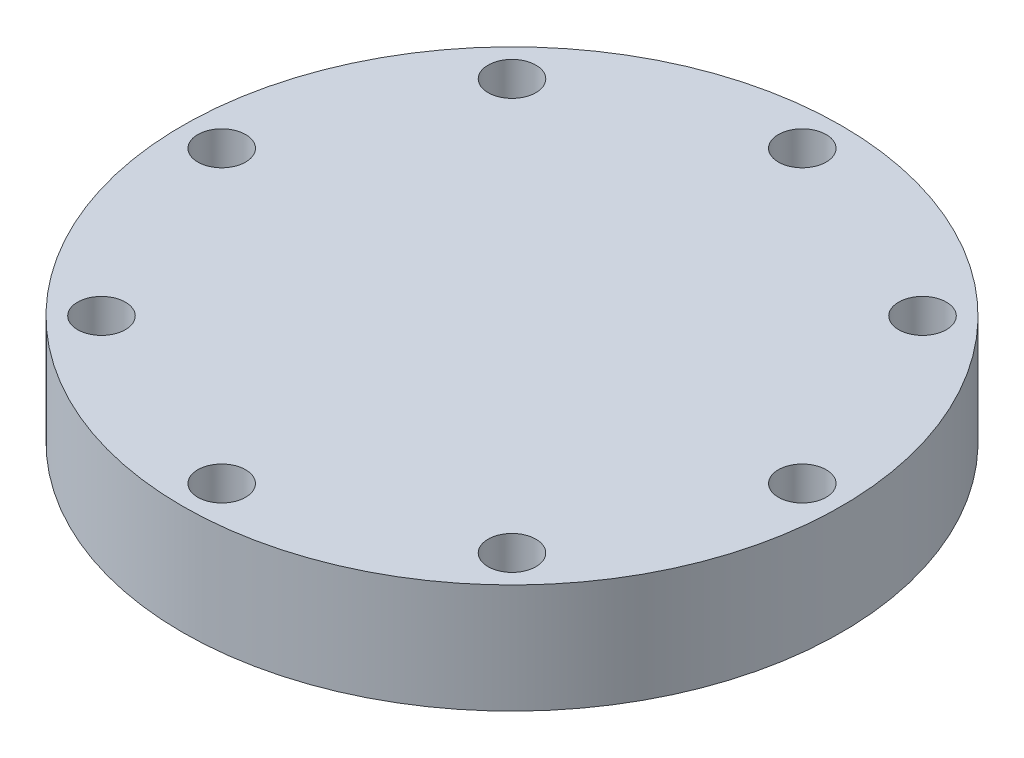
SolidWorks part; units mm, degrees
ref_plane "Front Plane" through (0, 0, 0) normal (0, 0, 1) x (1, 0, 0)
ref_plane "Top Plane" through (0, 0, 0) normal (0, 1, 0) x (1, 0, 0)
ref_plane "Right Plane" through (0, 0, 0) normal (1, 0, 0) x (0, 0, -1)
sketch "Sketch1" plane through (0, 0, 0) normal (0, 1, 0) x (1, 0, 0)
  circle A0 centre (0, 0) radius 48.25
  circle A1 centre (0, 0) radius 36
extrude "Boss-Extrude6" add sketch "Sketch1" along normal blind 10
sketch "Sketch19" plane through (0, 0, 0) normal (0, 1, 0) x (1, 0, 0)
  circle A0 centre (0, 0) radius 29.5
  circle A1 centre (0, 17.25) radius 3.5
  circle A2 centre (14.9389, 8.625) radius 3.5
  circle A3 centre (14.9389, -8.625) radius 3.5
  circle A4 centre (0, -17.25) radius 3.5
  circle A5 centre (-14.9389, -8.625) radius 3.5
  circle A6 centre (-14.9389, 8.625) radius 3.5
  point P18 (0, 0)
  dimension "D1" = 17.25
  dimension "D2" = 7
  dimension "D3" = 6
sketch "Sketch21" plane through (0, 10, 0) normal (0, 1, 0) x (1, 0, 0)
  circle A0 centre (-42.5, 0) radius 2
  dimension "D1" = 42.5
extrude "Cut-Extrude1" cut sketch "Sketch21" against normal blind 18 contours A0
pattern_circular "CirPattern1" count 8 every 45 about axis through (0, 0, 0) along (0, 1, 0) of "Cut-Extrude1"
sketch "Sketch22" plane through (0, 10, 0) normal (0, 1, 0) x (1, 0, 0)
  circle A0 centre (-42.5, 0) radius 3.5
extrude "Cut-Extrude2" cut sketch "Sketch22" against normal blind 4 contours A0
pattern_circular "CirPattern2" count 8 every 45 about axis through (0, 0, 0) along (0, 1, 0) of "Cut-Extrude2"
sketch "Sketch23" plane through (0, 10, 0) normal (0, 1, 0) x (1, 0, 0)
  circle A0 centre (0, 0) radius 48.25
extrude "Boss-Extrude7" add sketch "Sketch23" along normal blind 6
sketch "Sketch25" plane through (0, 10, 0) normal (0, -1, 0) x (1, 0, 0)
  circle A0 centre (-42.5, 0) radius 3.5
extrude "Cut-Extrude3" cut sketch "Sketch25" against normal blind 6 contours A0
pattern_circular "CirPattern4" count 8 every 45 about axis through (0, 10, 0) along (0, -1, 0) of "Cut-Extrude3"
